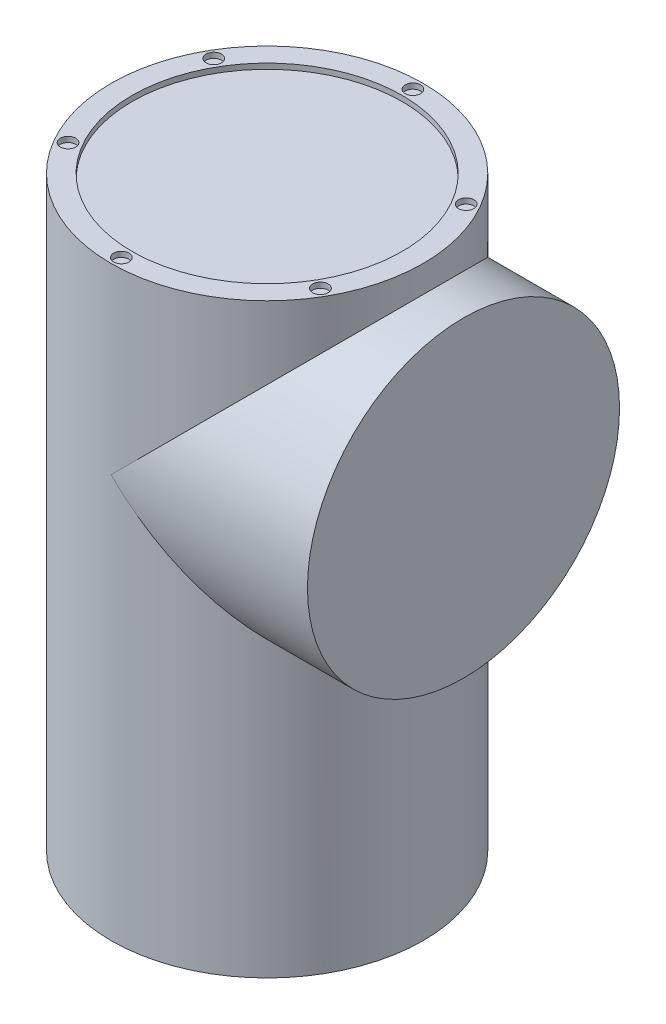
SolidWorks part; units mm, degrees
ref_plane "Alzado" through (0, 0, 0) normal (0, 0, 1) x (1, 0, 0)
ref_plane "Planta" through (0, 0, 0) normal (0, 1, 0) x (1, 0, 0)
ref_plane "Vista lateral" through (0, 0, 0) normal (1, 0, 0) x (0, 0, -1)
sketch "Croquis2" plane through (0, 0, 0) normal (0, 0, 1) x (1, 0, 0)
  line L0 (0, 0) -> (-67.5, 0)
  line L1 (-67.5, 0) -> (-67.5, 26.6893)
  line L2 (-67.5, 26.6893) -> (-58, 80)
  line L3 (-58, 80) -> (-58, 296)
  line L4 (-58, 296) -> (0, 296)
  line L5 (0, 296) -> (0, 0)
  point P3 (-67.5, 26.6893)
  dimension "D1" = 67.5
  dimension "D2" = 80
  dimension "D3" = 216
  dimension "D4" = 58
revolve "Revolución1" add sketch "Croquis2" angle 360 about L5
sketch "Croquis3" plane through (0, 296, 0) normal (0, 1, 0) x (1, 0, 0)
  line L0 (0, 58) -> (-8.9094, 66.9094)
  line L1 (-8.9094, 66.9094) -> (8.9094, 66.9094)
  line L2 (8.9094, 66.9094) -> (0, 58)
  line L6 (66.9094, -8.9094) -> (58, 0)
  line L7 (58, 0) -> (66.9094, 8.9094)
  line L8 (66.9094, 8.9094) -> (66.9094, -8.9094)
  line L9 (-8.9094, -66.9094) -> (0, -58)
  line L10 (0, -58) -> (8.9094, -66.9094)
  line L11 (8.9094, -66.9094) -> (-8.9094, -66.9094)
  line L12 (-66.9094, 8.9094) -> (-58, 0)
  line L13 (-58, 0) -> (-66.9094, -8.9094)
  line L14 (-66.9094, -8.9094) -> (-66.9094, 8.9094)
  circle A0 centre (0, 0) radius 58 construction
  circle A1 centre (0, 0) radius 58 construction
  circle A2 centre (0, 0) radius 67.5 construction
  point P8 (6.2889, 66.9094)
  point P21 (0, 0)
  dimension "D2" = 90
  dimension "D1" = 4
extrude "Cortar-Extruir4" cut sketch "Croquis3" against normal through all
sketch "Croquis4" plane through (0, 0, 0) normal (0, -1, 0) x (1, 0, 0)
  circle A0 centre (0, 0) radius 67.5
extrude "Saliente-Extruir1" add sketch "Croquis4" against normal blind 30
sketch "Croquis5" plane through (0, 296, 0) normal (0, 1, 0) x (1, 0, 0)
  circle A0 centre (0, 0) radius 58
  circle A1 centre (0, 0) radius 50.2278
  circle A2 centre (0, 54.1728) radius 2.8609
  circle A3 centre (46.9151, 27.0864) radius 2.8609
  circle A4 centre (46.9151, -27.0864) radius 2.8609
  circle A5 centre (0, -54.1728) radius 2.8609
  circle A6 centre (-46.9151, -27.0864) radius 2.8609
  circle A7 centre (-46.9151, 27.0864) radius 2.8609
  point P18 (0, 0)
  dimension "D1" = 6
extrude "Saliente-Extruir2" add sketch "Croquis5" along normal blind 2
sketch "Croquis6" plane through (0, 0, 0) normal (1, 0, 0) x (0, 0, -1)
  line L1 (50.2278, 298) -> (-50.2278, 298) construction
  line L2 (-58, 298) -> (-58, 80) construction
  circle A0 centre (0, 230) radius 58
  point P2 (0, 233.4429)
  point P7 (0, 230)
  dimension "D1" = 116
  dimension "D2" = 68
extrude "Saliente-Extruir3" add sketch "Croquis6" along normal blind 73
sketch "Croquis7" plane through (0, 0, 0) normal (1, 0, 0) x (0, 0, -1)
  line L0 (-100.6779, 80) -> (112.1475, 80)
  line L5 (112.1475, 80) -> (112.1475, -4.9904)
  line L6 (112.1475, -4.9904) -> (-100.6779, -4.9904)
  line L7 (-100.6779, -4.9904) -> (-100.6779, 80)
extrude "Cortar-Extruir5" cut sketch "Croquis7" against normal through all and the other way through all
